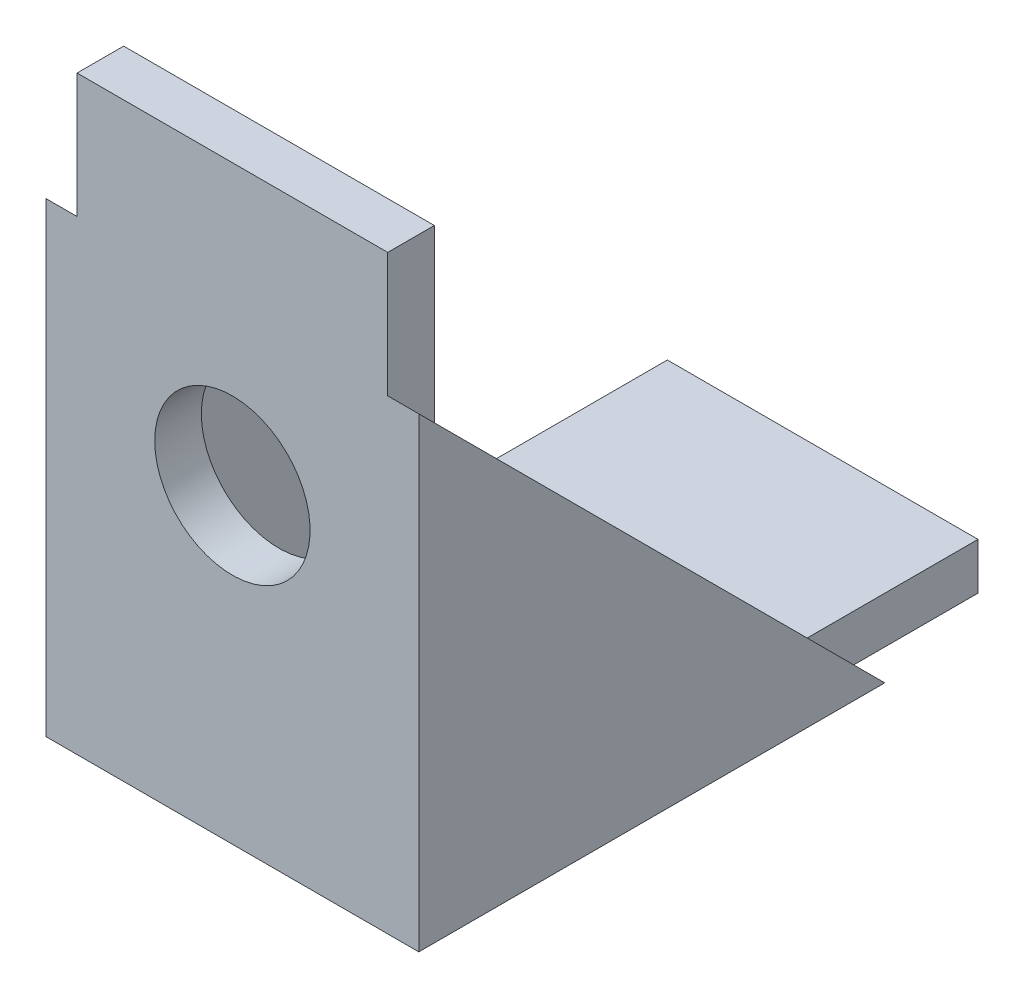
SolidWorks part; units mm, degrees
material "6063-O"
ref_plane "Front" through (0, 0, 0) normal (0, 0, 1) x (1, 0, 0)
ref_plane "Top" through (0, 0, 0) normal (0, 1, 0) x (1, 0, 0)
ref_plane "Right" through (0, 0, 0) normal (1, 0, 0) x (0, 0, -1)
sketch "草图1" plane through (0, 0, 0) normal (1, 0, 0) x (0, 0, -1)
  line L0 (0, 0) -> (0, 38)
  line L1 (0, 38) -> (3, 38)
  line L2 (3, 38) -> (3, 3)
  line L3 (3, 3) -> (38, 3)
  line L4 (38, 3) -> (38, 0)
  line L5 (38, 0) -> (0, 0)
  dimension "D1" = 38
  dimension "D2" = 3
  dimension "D3" = 35
  dimension "D4" = 35
extrude "凸台-拉伸1" add sketch "草图1" along normal blind 20
ref_plane "基准面1" through (20, 3, -38) normal (-1, 0, 0) x (0, 0, 1)
sketch "草图3" plane through (0, 3, 0) normal (0, 1, 0) x (1, 0, 0)
  line L0 (10, 38) -> (10, 0) construction
  line L1 (20, 38) -> (0, 38) construction
  line L2 (20, 0) -> (0, 0) construction
  circle A0 centre (16, 12) radius 1.5
  circle A1 centre (4, 12) radius 1.5
  circle A2 centre (4, 24) radius 1.5
  circle A3 centre (16, 24) radius 1.5
  dimension "D1" = 3
  dimension "D2" = 3
  dimension "D3" = 12
  dimension "D4" = 12
  dimension "D6" = 12
  dimension "D5" = 2
extrude "切除-拉伸1" cut sketch "草图3" against normal through all
sketch "草图4" plane through (0, 0, -38) normal (0, 0, -1) x (-1, 0, 0)
  line L4 (0, 0) -> (0, 3)
  line L5 (0, 3) -> (-20, 3)
  line L6 (-20, 3) -> (-20, 0)
  line L7 (-20, 0) -> (0, 0)
  line L8 (0, 0) -> (0, 3)
  line L9 (0, 3) -> (-20, 3)
  line L10 (-20, 3) -> (-20, 0)
  line L11 (-20, 0) -> (0, 0)
  dimension "D1" = 0
sketch "草图5" plane through (0, 0, -3) normal (0, 0, -1) x (-1, 0, 0)
  line L0 (-10, 38) -> (-10, 0) construction
  line L1 (-20, 38) -> (0, 38) construction
  line L3 (-20, 0) -> (0, 0) construction
  circle A0 centre (-10, 20) radius 5
  dimension "D1" = 10
  dimension "D2" = 20
extrude "切除-拉伸3" cut sketch "草图5" against normal through all
sketch "草图6" plane through (0, 0, 0) normal (-1, 0, 0) x (0, 0, 1)
  line L0 (0, 0) -> (0, 30)
  line L1 (0, 38) -> (0, 0) construction
  line L2 (0, 30) -> (-30, 0)
  line L3 (0, 0) -> (-38, 0) construction
  line L4 (-30, 0) -> (0, 0)
  dimension "D1" = 30
  dimension "D2" = 30
extrude "凸台-拉伸2" add sketch "草图6" along normal blind 2
sketch "草图7" plane through (20, 0, 0) normal (1, 0, 0) x (0, 0, -1)
  line L0 (0, 0) -> (0, 30)
  line L1 (0, 38) -> (0, 0) construction
  line L2 (0, 30) -> (30, 0)
  line L3 (30, 0) -> (0, 0)
  dimension "D1" = 30
extrude "凸台-拉伸3" add sketch "草图7" along normal blind 2
